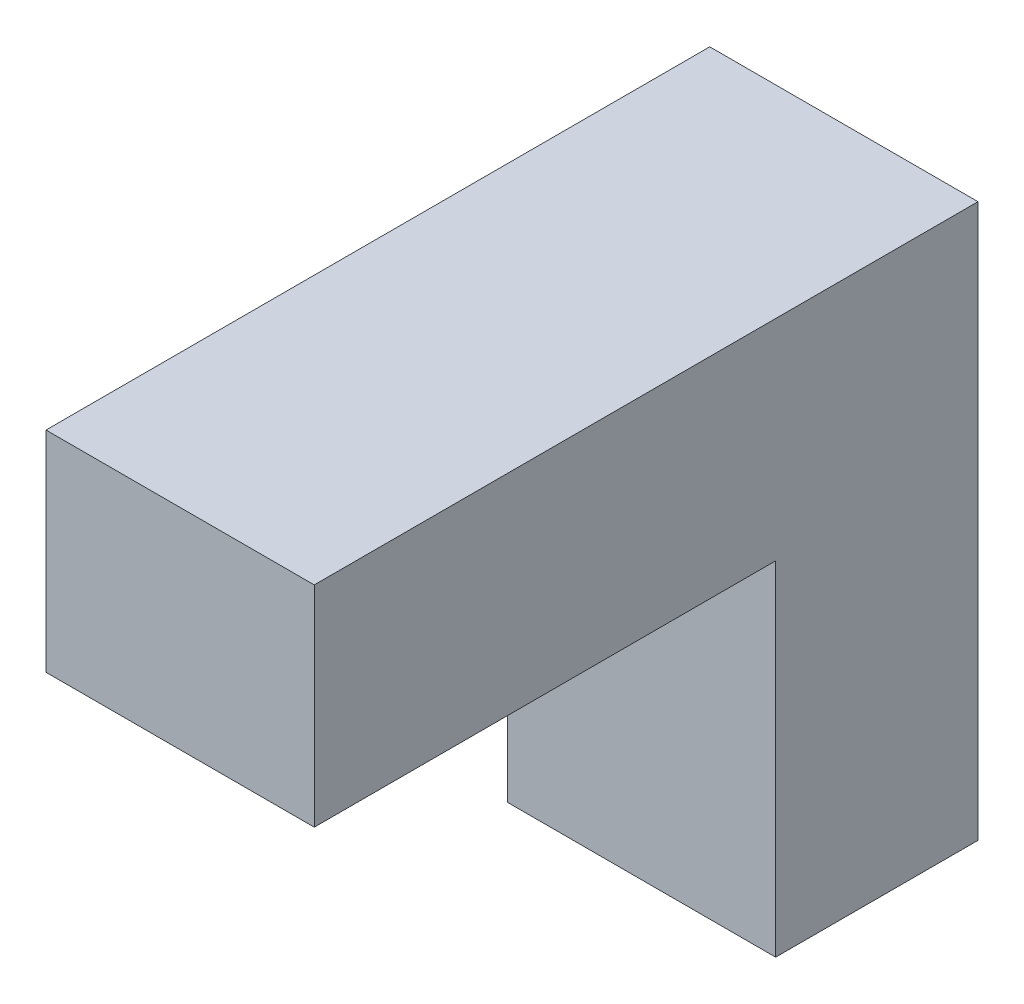
SolidWorks part; units mm, degrees
ref_plane "前基準面" through (0, 0, 0) normal (0, 0, 1) x (1, 0, 0)
ref_plane "上基準面" through (0, 0, 0) normal (0, 1, 0) x (1, 0, 0)
ref_plane "右基準面" through (0, 0, 0) normal (1, 0, 0) x (0, 0, -1)
sketch "草圖1" plane through (0, 0, 0) normal (1, 0, 0) x (0, 0, -1)
  line L0 (0, 0) -> (0, 20)
  line L1 (0, 20) -> (-24, 20)
  line L2 (-24, 20) -> (-24, 12.4126)
  line L3 (-24, 12.4126) -> (-7.3164, 12.4126)
  line L4 (-7.3164, 12.4126) -> (-7.3164, 0)
  line L5 (-7.3164, 0) -> (0, 0)
  dimension "D1" = 24
  dimension "D2" = 20
extrude "填料-伸長1" add sketch "草圖1" along normal blind 9.7
sketch "草圖2" plane through (0, 0, 0) normal (0, -1, 0) x (1, 0, 0)
  line L8 (1, 6.3164) -> (1, 1)
  line L9 (1, 1) -> (8.7, 1)
  line L10 (8.7, 1) -> (8.7, 6.3164)
  line L11 (8.7, 6.3164) -> (1, 6.3164)
  line L12 (1, 6.3164) -> (1, 1)
  line L13 (1, 1) -> (8.7, 1)
  line L14 (8.7, 1) -> (8.7, 6.3164)
  line L15 (8.7, 6.3164) -> (1, 6.3164)
  dimension "D1" = 1
extrude "除料-伸長1" cut sketch "草圖2" against normal offset from surface (17 mm away) 3 up to face at (4.85, 20, 12)
